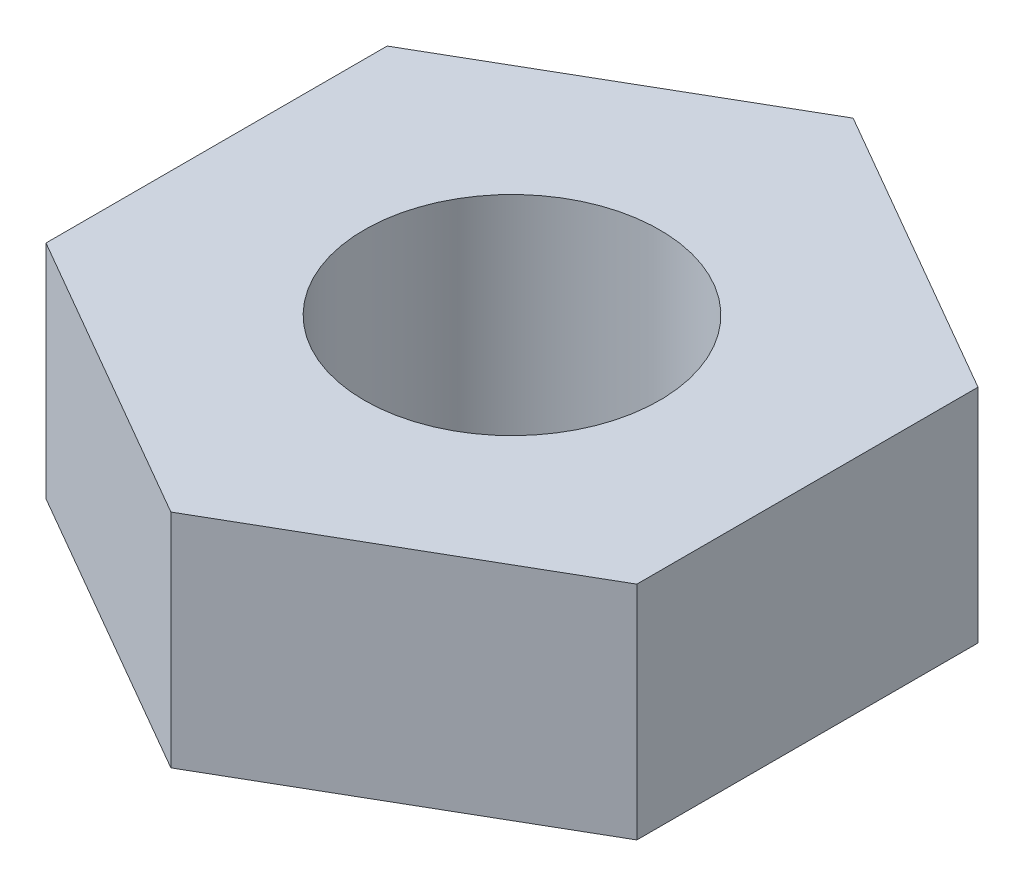
SolidWorks part; units mm, degrees
ref_plane "Front Plane" through (0, 0, 0) normal (0, 0, 1) x (1, 0, 0)
ref_plane "Top Plane" through (0, 0, 0) normal (0, 1, 0) x (1, 0, 0)
ref_plane "Right Plane" through (0, 0, 0) normal (1, 0, 0) x (0, 0, -1)
sketch "Sketch1" plane through (0, 0, 0) normal (0, 1, 0) x (1, 0, 0)
  line L1 (0, 2.3094) -> (-2, 1.1547)
  line L2 (-2, 1.1547) -> (-2, -1.1547)
  line L3 (-2, -1.1547) -> (0, -2.3094)
  line L4 (0, -2.3094) -> (2, -1.1547)
  line L5 (2, -1.1547) -> (2, 1.1547)
  line L6 (2, 1.1547) -> (0, 2.3094)
  circle A0 centre (0, 0) radius 1
  circle A1 centre (0, 0) radius 2 construction
  dimension "D1" = 2
  dimension "D2" = 4
extrude "Boss-Extrude1" add sketch "Sketch1" along normal blind 1.5
